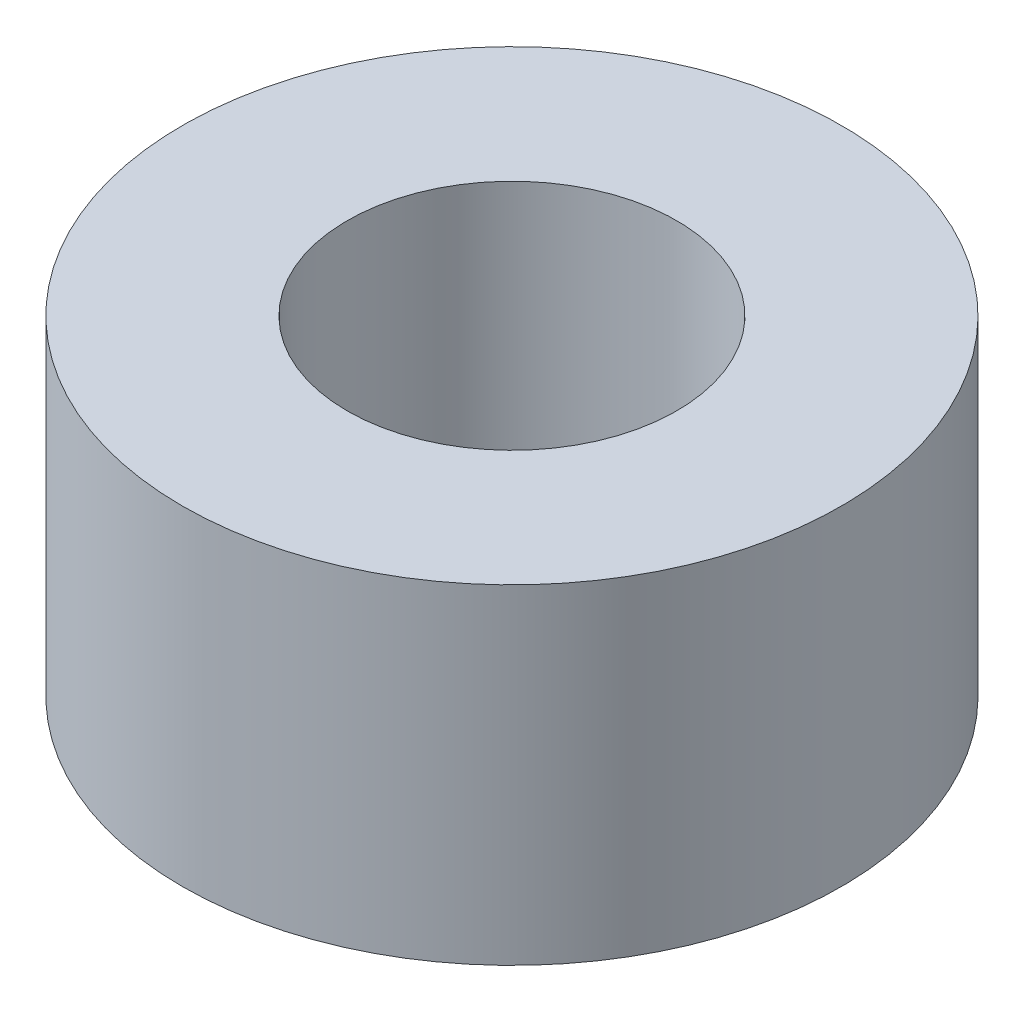
SolidWorks part; units mm, degrees
ref_plane "Front Plane" through (0, 0, 0) normal (0, 0, 1) x (1, 0, 0)
ref_plane "Top Plane" through (0, 0, 0) normal (0, 1, 0) x (1, 0, 0)
ref_plane "Right Plane" through (0, 0, 0) normal (1, 0, 0) x (0, 0, -1)
sketch "Sketch1" plane through (0, 0, 0) normal (0, 1, 0) x (1, 0, 0)
  circle A0 centre (0, 0) radius 3
extrude "Boss-Extrude1" add sketch "Sketch1" along normal blind 3
sketch "Sketch2" plane through (0, 3, 0) normal (0, 1, 0) x (1, 0, 0)
  circle A0 centre (0, 0) radius 1.5
extrude "Cut-Extrude1" cut sketch "Sketch2" against normal blind 3
